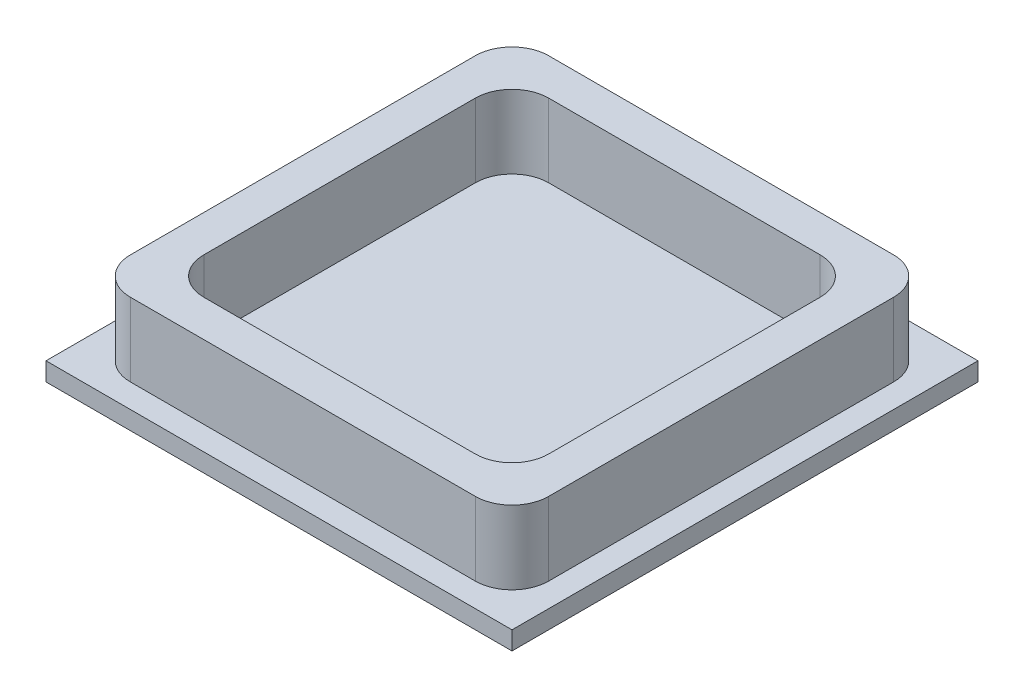
SolidWorks part; units mm, degrees
ref_plane "Front Plane" through (0, 0, 0) normal (0, 0, 1) x (1, 0, 0)
ref_plane "Top Plane" through (0, 0, 0) normal (0, 1, 0) x (1, 0, 0)
ref_plane "Right Plane" through (0, 0, 0) normal (1, 0, 0) x (0, 0, -1)
sketch "Sketch1" plane through (0, 0, 0) normal (0, 1, 0) x (1, 0, 0)
  line L1 (12.7, -12.7) -> (-12.7, -12.7)
  line L2 (12.7, -12.7) -> (12.7, 12.7)
  line L3 (12.7, 12.7) -> (-12.7, 12.7)
  line L4 (-12.7, -12.7) -> (-12.7, 12.7)
  line L5 (12.7, -12.7) -> (-12.7, 12.7) construction
  line L6 (12.7, 12.7) -> (-12.7, -12.7) construction
  point P0 (0, 0)
  dimension "D1" = 25.4
  dimension "D2" = 25.4
extrude "Boss-Extrude1" add sketch "Sketch1" along normal blind 1
sketch "Sketch2" plane through (0, 1, 0) normal (0, 1, 0) x (1, 0, 0)
  line L0 (-12.7, 12.7) -> (-12.7, -12.7) construction
  line L1 (-11.4, 11.4) -> (11.4, 11.4)
  line L2 (-11.4, 11.4) -> (-11.4, -11.4)
  line L3 (-11.4, -11.4) -> (11.4, -11.4)
  line L4 (11.4, 11.4) -> (11.4, -11.4)
  line L5 (-11.4, 11.4) -> (11.4, -11.4) construction
  line L6 (-11.4, -11.4) -> (11.4, 11.4) construction
  line L7 (12.7, 12.7) -> (-12.7, 12.7) construction
  line L8 (-9.4, 9.4) -> (-9.4, -9.4)
  line L9 (-9.4, -9.4) -> (9.4, -9.4)
  line L10 (9.4, 9.4) -> (9.4, -9.4)
  line L11 (-9.4, 9.4) -> (9.4, 9.4)
  point P0 (0, 0)
  dimension "D1" = 1.3
  dimension "D2" = 1.3
  dimension "D3" = 2
extrude "Boss-Extrude2" add sketch "Sketch2" along normal blind 4
fillet "Fillet1" radius 2 8 edges at (-9.4, 3, 9.4) (9.4, 3, 9.4) (9.4, 3, -9.4) (-9.4, 3, -9.4) (-11.4, 3, 11.4) (11.4, 3, 11.4) (11.4, 3, -11.4) (-11.4, 3, -11.4)
